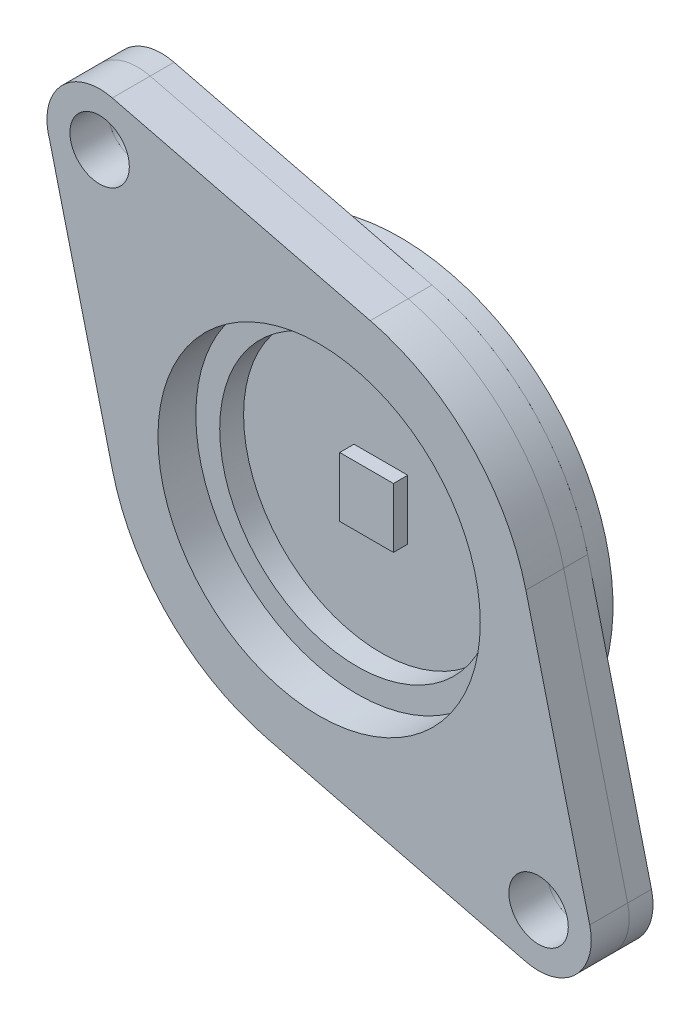
SolidWorks part; units mm, degrees
ref_plane "Front Plane" through (0, 0, 0) normal (0, 0, 1) x (1, 0, 0)
ref_plane "Top Plane" through (0, 0, 0) normal (0, 1, 0) x (1, 0, 0)
ref_plane "Right Plane" through (0, 0, 0) normal (1, 0, 0) x (0, 0, -1)
sketch "Sketch1" plane through (0, 0, 0) normal (0, 0, 1) x (1, 0, 0)
  line L0 (-22.5732, 16.9951) -> (-17.3222, -4.2762)
  line L1 (23.8125, -23.8125) -> (-23.8125, -23.8125) construction
  line L2 (23.8125, -23.8125) -> (23.8125, 23.8125) construction
  line L3 (23.8125, 23.8125) -> (-23.8125, 23.8125) construction
  line L4 (-23.8125, -23.8125) -> (-23.8125, 23.8125) construction
  line L5 (23.8125, -23.8125) -> (-23.8125, 23.8125) construction
  line L6 (23.8125, 23.8125) -> (-23.8125, -23.8125) construction
  line L7 (-17.3245, 22.6685) -> (4.2867, 17.3196)
  line L8 (17.3196, 4.2867) -> (22.6685, -17.3245)
  line L9 (-4.2867, -17.3196) -> (17.3245, -22.6685)
  circle A0 centre (0, 0) radius 21.75 construction
  circle A1 centre (0, 0) radius 26 construction
  circle A2 centre (-18.3848, 18.3848) radius 2.413 construction
  circle A3 centre (18.3848, -18.3848) radius 3.0643 construction
  arc A4 (-17.3245, 22.6685) -> (-22.5732, 16.9951) centre (-18.3848, 18.3848) ccw
  arc A5 (17.3245, -22.6685) -> (22.6685, -17.3245) centre (18.3848, -18.3848) ccw
  arc A6 (-17.3222, -4.2762) -> (-4.2867, -17.3196) centre (0, 0) ccw
  circle A7 centre (0, 0) radius 13.5
  arc A8 (17.3196, 4.2867) -> (4.2867, 17.3196) centre (0, 0) ccw
  dimension "D1" = 43.5
  dimension "D2" = 52
  dimension "D4" = 4.826
  dimension "D5" = 27
  dimension "D6" = 2
  dimension "D3" = 47.625
extrude "Boss-Extrude1" add sketch "Sketch1" along normal blind 3.175
hole_wizard "#10 Clearance Hole1" positions "Sketch2" profile "Sketch3" hole size "#10" standard "ANSI Inch" end condition through all
sketch "Sketch2" plane through (0, 0, 3.175) normal (0, 0, 1) x (1, 0, 0)
  point P0 (-18.3848, 18.3848)
  point P3 (18.3848, -18.3848)
sketch "Sketch3" plane through (-18.3848, 18.3848, 3.175) normal (1, 0, 0) x (0, -1, 0)
  line L0 (0, 0) -> (0, 3.175)
  line L1 (0, 3.175) -> (2.4892, 3.175)
  line L2 (2.4892, 3.175) -> (2.4892, 0)
  line L5 (2.4892, 0) -> (0, 0)
  line L11 (0, -6.35) -> (0, 107.95) construction
  dimension "Thru Hole Dia." = 4.9784
  dimension "Thru Hole Depth" = 3.175
sketch "Sketch6" plane through (0, 0, 0) normal (0, 0, -1) x (-1, 0, 0)
  line L4 (17.3245, 22.6685) -> (-4.2867, 17.3196)
  line L5 (-17.3196, 4.2867) -> (-22.6685, -17.3245)
  line L6 (-17.3245, -22.6685) -> (4.2867, -17.3196)
  line L7 (17.3222, -4.2762) -> (22.5732, 16.9951)
  line L8 (17.3245, 22.6685) -> (-4.2867, 17.3196)
  line L9 (-17.3196, 4.2867) -> (-22.6685, -17.3245)
  line L10 (-17.3245, -22.6685) -> (4.2867, -17.3196)
  line L11 (17.3222, -4.2762) -> (22.5732, 16.9951)
  circle A0 centre (0, 0) radius 11.5
  circle A1 centre (0, 0) radius 13.5 construction
  circle A3 centre (-18.3848, -18.3848) radius 2.4892
  circle A4 centre (-18.3848, -18.3848) radius 2.4892
  circle A5 centre (18.3848, 18.3848) radius 2.4892
  circle A6 centre (18.3848, 18.3848) radius 2.4892
  arc A10 (22.5732, 16.9951) -> (17.3245, 22.6685) centre (18.3848, 18.3848) ccw
  arc A11 (-4.2867, 17.3196) -> (-17.3196, 4.2867) centre (0, 0) ccw
  arc A12 (-22.6685, -17.3245) -> (-17.3245, -22.6685) centre (-18.3848, -18.3848) ccw
  arc A13 (4.2867, -17.3196) -> (17.3222, -4.2762) centre (0, 0) ccw
  arc A14 (22.5732, 16.9951) -> (17.3245, 22.6685) centre (18.3848, 18.3848) ccw
  arc A15 (-4.2867, 17.3196) -> (-17.3196, 4.2867) centre (0, 0) ccw
  arc A16 (-22.6685, -17.3245) -> (-17.3245, -22.6685) centre (-18.3848, -18.3848) ccw
  arc A17 (4.2867, -17.3196) -> (17.3222, -4.2762) centre (0, 0) ccw
  dimension "D1" = 2
  dimension "D2" = 0
  dimension "D3" = 0
  dimension "D4" = 0
extrude "Boss-Extrude4" add sketch "Sketch6" along normal blind 2 separate body
sketch "Sketch4" plane through (0, 0, -2) normal (0, 0, -1) x (-1, 0, 0)
  line L4 (17.3245, 22.6685) -> (-4.2867, 17.3196)
  line L5 (-17.3196, 4.2867) -> (-22.6685, -17.3245)
  line L6 (-17.3245, -22.6685) -> (4.2867, -17.3196)
  line L7 (17.3222, -4.2762) -> (22.5732, 16.9951)
  arc A10 (22.5732, 16.9951) -> (17.3245, 22.6685) centre (18.3848, 18.3848) ccw
  arc A11 (-4.2867, 17.3196) -> (-17.3196, 4.2867) centre (0, 0) ccw
  arc A12 (-22.6685, -17.3245) -> (-17.3245, -22.6685) centre (-18.3848, -18.3848) ccw
  arc A13 (4.2867, -17.3196) -> (17.3222, -4.2762) centre (0, 0) ccw
  arc A15 (17.3222, -4.2762) -> (4.2867, -17.3196) centre (0, 0) ccw
  arc A17 (4.2867, -17.3196) -> (17.3222, -4.2762) centre (0, 0) ccw
  dimension "D4" = 0
extrude "Boss-Extrude2" add sketch "Sketch4" along normal blind 1.6 separate body
sketch "Sketch5" plane through (0, 0, -2) normal (0, 0, 1) x (1, 0, 0)
  line L1 (2.25, -2.5) -> (-2.25, -2.5)
  line L2 (2.25, -2.5) -> (2.25, 2.5)
  line L3 (2.25, 2.5) -> (-2.25, 2.5)
  line L4 (-2.25, -2.5) -> (-2.25, 2.5)
  line L5 (2.25, -2.5) -> (-2.25, 2.5) construction
  line L6 (2.25, 2.5) -> (-2.25, -2.5) construction
  point P0 (0, 0)
  dimension "D1" = 4.5
  dimension "D2" = 5
extrude "Boss-Extrude3" add sketch "Sketch5" along normal blind 1.2 separate body
